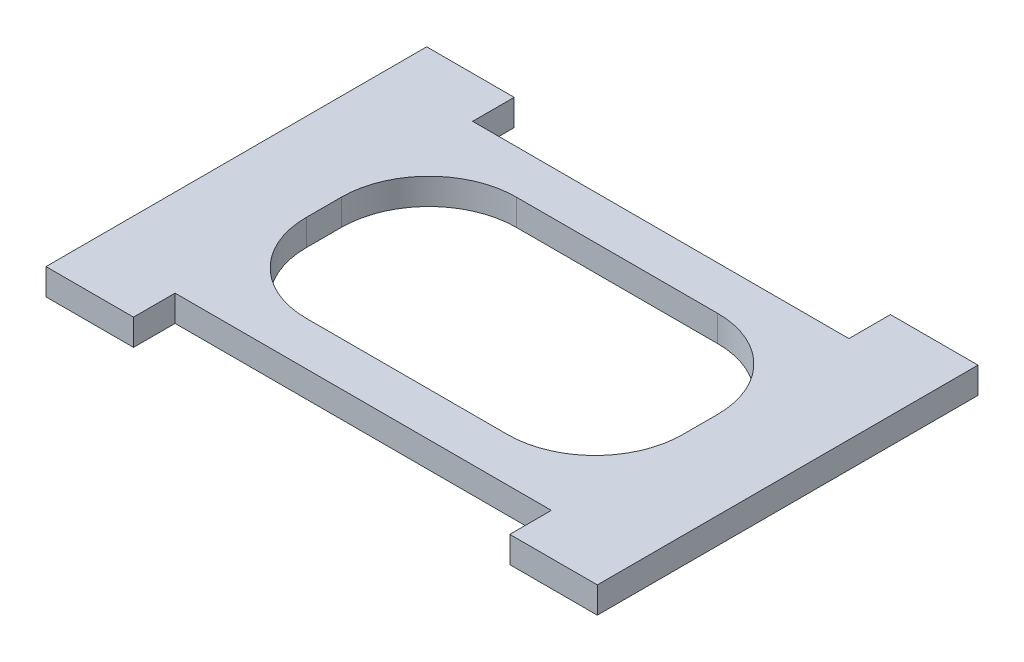
SolidWorks part; units mm, degrees
ref_plane "Front Plane" through (0, 0, 0) normal (0, 0, 1) x (1, 0, 0)
ref_plane "Top Plane" through (0, 0, 0) normal (0, 1, 0) x (1, 0, 0)
ref_plane "Right Plane" through (0, 0, 0) normal (1, 0, 0) x (0, 0, -1)
sketch "Sketch1" plane through (0, 0, 0) normal (0, 1, 0) x (1, 0, 0)
  line L0 (12.75, 17) -> (12.75, -17)
  line L5 (0, 0) -> (-50.25, 13.2957) construction
  line L6 (0, 0) -> (-50.25, -13.2957) construction
  line L7 (2.75, -17) -> (-40.25, -17)
  line L8 (-50.25, 17) -> (-50.25, -17)
  line L10 (2.75, -17) -> (-40.25, -17)
  line L14 (-50.25, -17) -> (-50.25, -21.75)
  line L15 (-50.25, -21.75) -> (-40.25, -21.75)
  line L16 (-40.25, -17) -> (-40.25, -21.75)
  line L18 (2.75, -17) -> (2.75, -21.75)
  line L19 (2.75, -21.75) -> (12.75, -21.75)
  line L20 (12.75, -17) -> (12.75, -21.75)
  line L26 (-50.25, 17) -> (-50.25, 21.75)
  line L27 (-50.25, 21.75) -> (-40.25, 21.75)
  line L28 (-40.25, 17) -> (-40.25, 21.75)
  line L30 (2.75, 17) -> (2.75, 21.75)
  line L31 (2.75, 21.75) -> (12.75, 21.75)
  line L32 (12.75, 17) -> (12.75, 21.75)
  line L37 (2.75, 17) -> (-40.25, 17)
  point P0 (0, 0)
  dimension "D6" = 10
  dimension "D7" = 43
  dimension "D8" = 10
  dimension "D9" = 4.75
extrude "Boss-Extrude1" add sketch "Sketch1" along normal blind 3
sketch "Sketch5" plane through (0, 3, 0) normal (0, 1, 0) x (1, 0, 0)
  line L4 (-40.25, 12) -> (2.75, 12)
  line L5 (-40.25, 12) -> (-40.25, -12)
  line L6 (-40.25, -12) -> (2.75, -12)
  line L7 (2.75, 12) -> (2.75, -12)
extrude "Cut-Extrude4" cut sketch "Sketch5" against normal blind 3 contours L5 L4 L7 L6
fillet "Fillet1" radius 10 4 edges at (2.75, 1.5, 12) (2.75, 1.5, -12) (-40.25, 1.5, -12) (-40.25, 1.5, 12)
